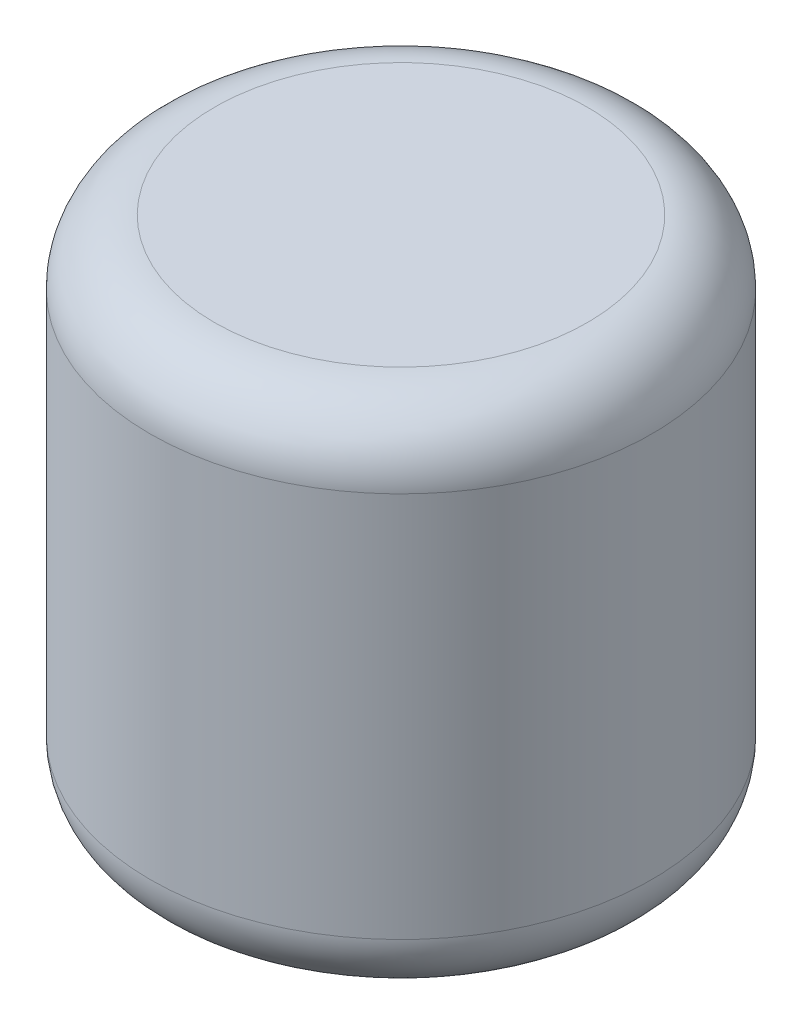
SolidWorks part; units mm, degrees
ref_plane "Front Plane" through (0, 0, 0) normal (0, 0, 1) x (1, 0, 0)
ref_plane "Top Plane" through (0, 0, 0) normal (0, 1, 0) x (1, 0, 0)
ref_plane "Right Plane" through (0, 0, 0) normal (1, 0, 0) x (0, 0, -1)
sketch "Sketch1" plane through (0, 0, 0) normal (0, 1, 0) x (1, 0, 0)
  circle A0 centre (0, 0) radius 49.53
  dimension "D1" = 99.06
extrude "Boss-Extrude1" add sketch "Sketch1" along normal blind 101.6 contours A0
fillet "Fillet1" radius 12.7 2 edges at (0, 0, 49.53) (0, 101.6, 49.53)
